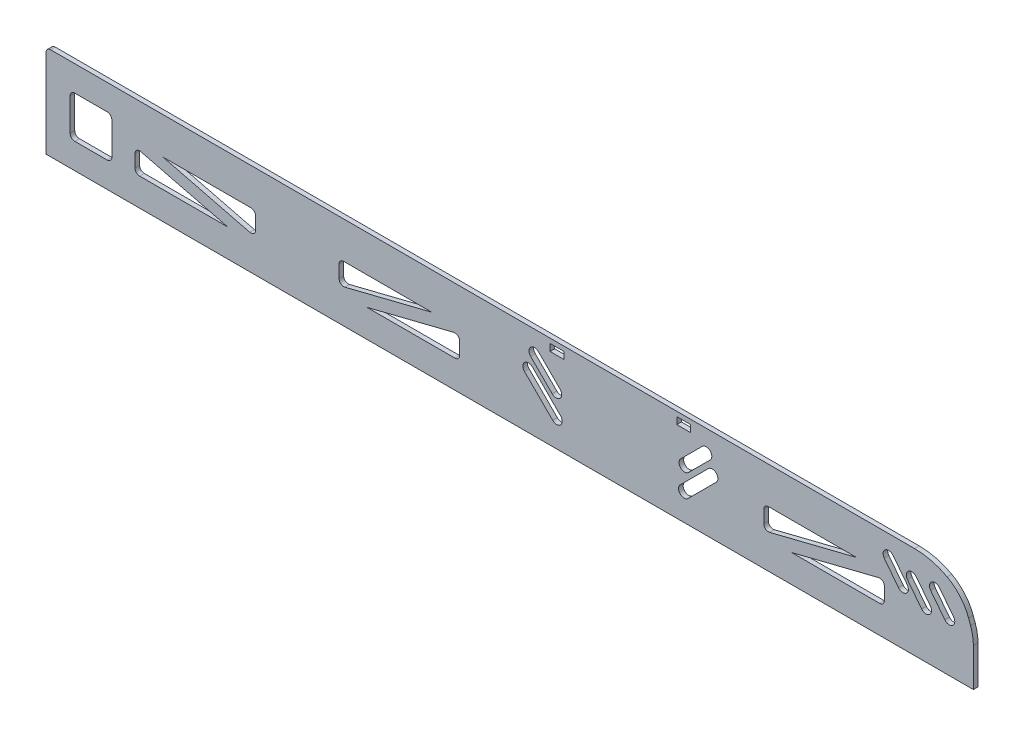
SolidWorks part; units mm, degrees
ref_plane "Front Plane" through (0, 0, 0) normal (0, 0, 1) x (1, 0, 0)
ref_plane "Top Plane" through (0, 0, 0) normal (0, 1, 0) x (1, 0, 0)
ref_plane "Right Plane" through (0, 0, 0) normal (1, 0, 0) x (0, 0, -1)
sketch "Sketch1" plane through (0, 0, 0) normal (0, 0, 1) x (1, 0, 0)
  line L0 (-200, 10) -> (-200, 20)
  line L1 (0, 0) -> (-200, 0) construction
  line L2 (0, 0) -> (0, 20) construction
  line L3 (0, 20) -> (-200, 20) construction
  line L4 (-200, 10) -> (-200, 20)
  line L5 (-100, 20) -> (-100, 0) construction
  line L6 (0, 10) -> (-200, 10) construction
  line L7 (-190, 0) -> (0, 0) construction
  line L8 (60.7449, 36.303) -> (260.1814, 21.3) construction
  line L9 (-180.8, 11) -> (-180.8, 6)
  line L10 (-194.8, 14.5) -> (-185.8, 14.5)
  line L11 (-194.8, 14.5) -> (-194.8, 5.5)
  line L12 (-194.8, 5.5) -> (-185.8, 5.5)
  line L13 (-185.8, 14.5) -> (-185.8, 5.5)
  line L14 (-190.3, 5.5) -> (-190.3, 14.5) construction
  line L15 (-194.8, 10) -> (-185.8, 10) construction
  line L16 (-180.8, 6) -> (-160.8, 6)
  line L17 (-160.8, 6) -> (-180.8, 11)
  line L18 (-175.1796, 10.8834) -> (-154.8, 5.7885) construction
  line L19 (-154.8, 7.0769) -> (-154.8, 12.0769)
  line L20 (-154.8, 12.0769) -> (-174.8, 12.0769)
  line L21 (-174.8, 12.0769) -> (-154.8, 7.0769)
  line L22 (-145.8, 16.5491) -> (-145.8, 2.1149) construction
  line L23 (-130.8, 6) -> (-110.8, 11)
  line L24 (-110.8, 6) -> (-130.8, 6)
  line L25 (-110.8, 11) -> (-110.8, 6)
  line L26 (-136.8, 7.0769) -> (-136.8, 12.0769)
  line L27 (-116.8, 12.0769) -> (-136.8, 7.0769)
  line L28 (-136.8, 12.0769) -> (-116.8, 12.0769)
  line L29 (-95.9515, 11.8485) -> (-89.8704, 5.7674) construction
  line L30 (-95.1029, 12.6971) -> (-89.0218, 6.6159)
  line L31 (-96.8, 11) -> (-90.7189, 4.9189)
  line L32 (-94.6431, 15.3485) -> (-89.9762, 10.6816) construction
  line L33 (-93.7946, 16.1971) -> (-89.1277, 11.5302)
  line L34 (-95.4917, 14.5) -> (-90.8248, 9.8331)
  line L35 (-76.1277, 16.7406) -> (-76.1277, 1.5062) construction
  line L36 (-60.9608, 18.25) -> (-63.9608, 18.25) construction
  line L37 (-91.2946, 19) -> (-88.2946, 19)
  line L38 (-91.2946, 19) -> (-91.2946, 17.5)
  line L39 (-91.2946, 17.5) -> (-88.2946, 17.5)
  line L40 (-88.2946, 19) -> (-88.2946, 17.5)
  line L41 (-89.7946, 17.5) -> (-89.7946, 19) construction
  line L42 (-91.2946, 18.25) -> (-88.2946, 18.25) construction
  line L43 (-62.4608, 17.5) -> (-62.4608, 19) construction
  line L44 (-63.9608, 19) -> (-63.9608, 17.5)
  line L45 (-60.9608, 17.5) -> (-63.9608, 17.5)
  line L46 (-60.9608, 19) -> (-60.9608, 17.5)
  line L47 (-60.9608, 19) -> (-63.9608, 19)
  line L48 (-57.6123, 15.3485) -> (-62.2792, 10.6816) construction
  line L49 (-58.4608, 16.1971) -> (-63.1277, 11.5302)
  line L50 (-56.7638, 14.5) -> (-61.4307, 9.8331)
  line L51 (-56.304, 11.8485) -> (-62.3851, 5.7674) construction
  line L52 (-57.1525, 12.6971) -> (-63.2336, 6.6159)
  line L53 (-55.4554, 11) -> (-61.5365, 4.9189)
  line L54 (-24.8204, 10.8834) -> (-45.2, 5.7885) construction
  line L55 (-25.2, 12.0769) -> (-45.2, 7.0769)
  line L56 (-45.2, 12.0769) -> (-25.2, 12.0769)
  line L57 (-45.2, 7.0769) -> (-45.2, 12.0769)
  line L58 (-39.2, 6) -> (-19.2, 11)
  line L59 (-19.2, 6) -> (-39.2, 6)
  line L60 (-19.2, 11) -> (-19.2, 6)
  line L61 (-200, 10) -> (-200, 0)
  line L62 (-200, 0) -> (-190, 0)
  line L63 (-10, 0) -> (-200, 0)
  line L64 (0, 20) -> (0, 10) construction
  line L65 (-10, 0) -> (0, 0)
  line L66 (0, 0) -> (0, 10)
  line L67 (-12.6863, 20) -> (-200, 20)
  line L68 (0, 10) -> (0, 0)
  line L69 (0, 10) -> (-1.9431, 15.3485)
  line L70 (-18.2706, 15.6552) -> (-15.2087, 11.7024) construction
  line L71 (-17.322, 16.3901) -> (-14.26, 12.4373)
  line L72 (-19.2193, 14.9203) -> (-16.1574, 10.9675)
  line L73 (-13.2706, 14.1721) -> (-10.2087, 10.2194) construction
  line L74 (-12.322, 14.907) -> (-9.26, 10.9542)
  line L75 (-14.2193, 13.4373) -> (-11.1574, 9.4845)
  line L76 (-8.2706, 14.6419) -> (-5.2087, 10.6891) construction
  line L77 (-7.322, 15.3767) -> (-4.26, 11.424)
  line L78 (-9.2193, 13.907) -> (-6.1574, 9.9542)
  arc A0 (-1.9431, 15.3485) -> (-12.6863, 20) centre (-12.6863, 5.2678) ccw
  arc A1 (-95.1029, 12.6971) -> (-96.8, 11) centre (-95.9515, 11.8485) ccw
  arc A2 (-90.7189, 4.9189) -> (-89.0218, 6.6159) centre (-89.8704, 5.7674) ccw
  arc A3 (-93.7946, 16.1971) -> (-95.4917, 14.5) centre (-94.6431, 15.3485) ccw
  arc A4 (-90.8248, 9.8331) -> (-89.1277, 11.5302) centre (-89.9762, 10.6816) ccw
  arc A5 (-58.4608, 16.1971) -> (-56.7638, 14.5) centre (-57.6123, 15.3485) cw
  arc A6 (-61.4307, 9.8331) -> (-63.1277, 11.5302) centre (-62.2792, 10.6816) cw
  arc A7 (-57.1525, 12.6971) -> (-55.4554, 11) centre (-56.304, 11.8485) cw
  arc A8 (-61.5365, 4.9189) -> (-63.2336, 6.6159) centre (-62.3851, 5.7674) cw
  arc A9 (-17.322, 16.3901) -> (-19.2193, 14.9203) centre (-18.2706, 15.6552) ccw
  arc A10 (-16.1574, 10.9675) -> (-14.26, 12.4373) centre (-15.2087, 11.7024) ccw
  arc A11 (-12.322, 14.907) -> (-14.2193, 13.4373) centre (-13.2706, 14.1721) ccw
  arc A12 (-11.1574, 9.4845) -> (-9.26, 10.9542) centre (-10.2087, 10.2194) ccw
  arc A13 (-7.322, 15.3767) -> (-9.2193, 13.907) centre (-8.2706, 14.6419) ccw
  arc A14 (-6.1574, 9.9542) -> (-4.26, 11.424) centre (-5.2087, 10.6891) ccw
  point P30 (-92.9109, 8.808)
  point P35 (-92.3097, 13.0151)
  point P43 (-96.8, 12.6971)
  point P45 (-89.1277, 9.8331)
  point P58 (-62.4608, 18.25)
  point P61 (-59.9457, 13.0151)
  point P68 (-59.3445, 8.808)
  point P86 (-16.7397, 13.6788)
  point P91 (-11.7397, 12.1958)
  point P98 (-6.7397, 12.6655)
  point P104 (-89.7946, 18.25)
  point P110 (0, 0)
  point P111 (0, 0)
  point P112 (-15.3569, 13.599)
  point P113 (-15.0828, 14.295)
  point P114 (-16.7397, 13.6788)
  point P156 (-100, 10)
  point P158 (-190.3, 10)
  dimension "D3" = 200
  dimension "D12" = 11
  dimension "D13" = 9
  dimension "D14" = 1.2
  dimension "D27" = 1
  dimension "D28" = 1.2
  dimension "D1" = 200
  dimension "D2" = 20
  dimension "D4" = 9
  dimension "D5" = 5.2
  dimension "D6" = 9
  dimension "D7" = 20
  dimension "D8" = 5
  dimension "D9" = 5
  dimension "D10" = 1.25
  dimension "D11" = 9
  dimension "D15" = 14
  dimension "D16" = 45
  dimension "D17" = 1
  dimension "D18" = 13
  dimension "D19" = 3.5
  dimension "D20" = 3
  dimension "D21" = 1.5
  dimension "D22" = 1
  dimension "D23" = 2.5
  dimension "D24" = 6
  dimension "D25" = 70.034
  dimension "D26" = 1
  dimension "D29" = 5
  dimension "D30" = 5
  dimension "D31" = 5
extrude "Boss-Extrude1" add sketch "Sketch1" along normal mid plane 1 contours L69 A0 L67 L0 L61 L62 L63 L65 L66 A14 L78 A13 L77 A12 L75 A11 L74 A10 L72 A9 L71 A4 L34 A3 L33 A2 L31 A1 L30 L58 L60 L59 L55 L57 L56 L37 L40 L39 L38 L26 L28 L27
fillet "Fillet1" radius 10 2 edges at (-1.9431, 15.3485, 0) (0, 10, 0)
fillet "Fillet3" radius 1 17 edges at (-185.8, 5.5, 0) (-185.8, 14.5, 0) (-194.8, 14.5, 0) (-194.8, 5.5, 0) (-19.2, 11, 0) (-19.2, 6, 0) (-45.2, 7.0769, 0) (-45.2, 12.0769, 0) (-110.8, 11, 0) (-110.8, 6, 0) (-136.8, 12.0769, 0) (-136.8, 7.0769, 0) (-154.8, 12.0769, 0) (-154.8, 7.0769, 0) (-180.8, 11, 0) (-180.8, 6, 0) (-200, 20, 0)
